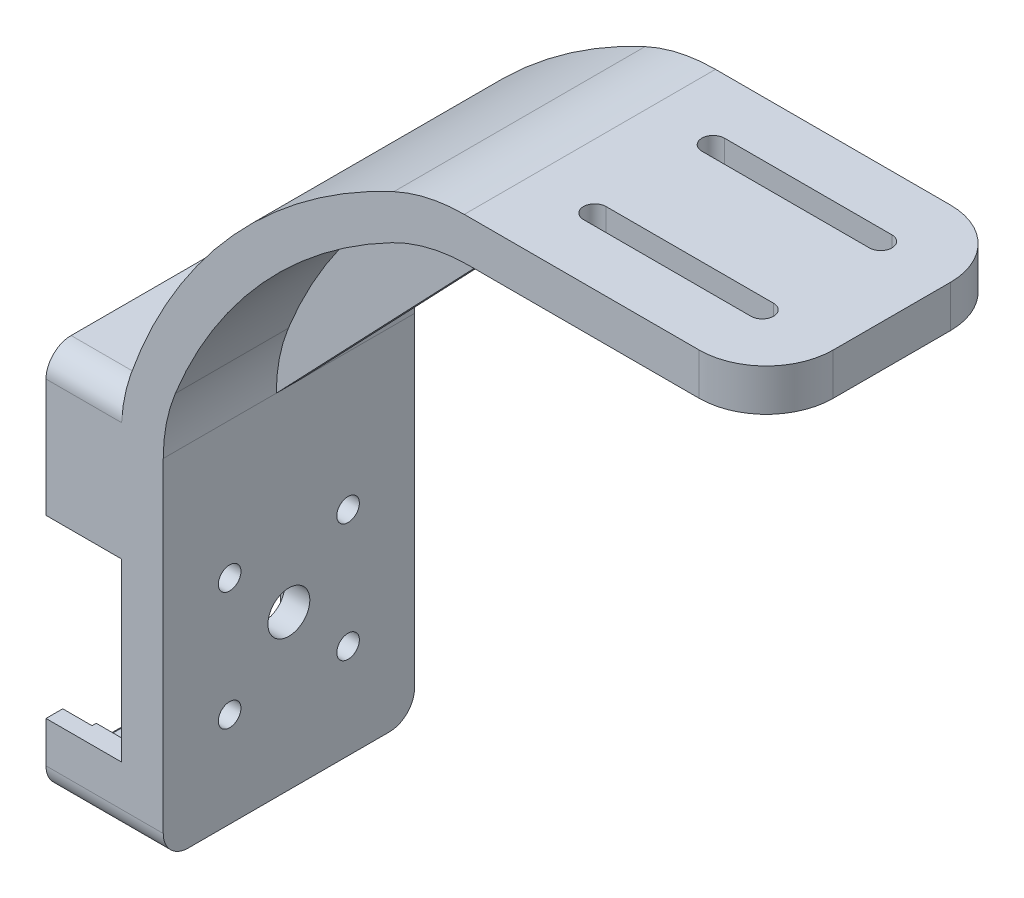
SolidWorks part; units mm, degrees
material "ABS"
ref_plane "Alzado" through (0, 0, 0) normal (0, 0, 1) x (1, 0, 0)
ref_plane "Planta" through (0, 0, 0) normal (0, 1, 0) x (1, 0, 0)
ref_plane "Vista lateral" through (0, 0, 0) normal (1, 0, 0) x (0, 0, -1)
sketch "Croquis1" plane through (0, 0, 0) normal (0, 0, 1) x (1, 0, 0)
  line L0 (7, 0) -> (7, 5)
  line L1 (7, 5) -> (-33, 5)
  line L2 (-33, 5) -> (-70, -35) construction
  line L3 (-70, -35) -> (-70, -80)
  line L4 (-70, -80) -> (-65, -80)
  line L5 (-65, -80) -> (-65, -34.8052)
  line L6 (-65, -34.8052) -> (-32.8052, 0) construction
  line L7 (-32.8052, 0) -> (7, 0)
  line L8 (-48.9026, -17.4026) -> (-12.1976, -51.3547) construction
  arc A0 (-33, 5) -> (-70, -35) centre (-12.1976, -51.3547) ccw
  arc A2 (-32.8052, 0) -> (-65, -34.8052) centre (-12.1976, -51.3547) ccw
  dimension "D1" = 5
  dimension "D2" = 37
  dimension "D4" = 5
  dimension "D5" = 40
  dimension "D6" = 45
  dimension "D7" = 40
  dimension "D8" = 50
extrude "Saliente-Extruir1" add sketch "Croquis1" along normal blind 30
sketch "Croquis2" plane through (0, 5, 0) normal (0, 1, 0) x (1, 0, 0)
  line L0 (7, -30) -> (7, 0) construction
  line L1 (-11.4, -15) -> (-11.4, -12) construction
  line L2 (-11.4, -12) -> (-4.4, -12) construction
  line L4 (-4.4, -18) -> (-18.4, -18) construction
  line L6 (-18.4, -12) -> (-11.4, -12) construction
  line L7 (-11.4, -15) -> (-11.4, -7.93) construction
  line L8 (-11.4, -7.93) -> (-11.4, -6.58) construction
  line L9 (-11.4, -6.58) -> (-1.4, -6.58)
  line L11 (-1.4, -9.28) -> (-21.4, -9.28)
  line L13 (-21.4, -6.58) -> (-11.4, -6.58)
  line L14 (-11.4, -15) -> (-21.0577, -15) construction
  line L15 (-1.4, -20.72) -> (-21.4, -20.72)
  line L16 (-11.4, -23.42) -> (-1.4, -23.42)
  line L17 (-21.4, -23.42) -> (-11.4, -23.42)
  line L18 (-11.4, -15) -> (7, -15) construction
  circle A0 centre (-11.4, -15) radius 18.4 construction
  arc A1 (-18.4, -18) -> (-18.4, -12) centre (-18.4, -15) cw construction
  arc A2 (-4.4, -18) -> (-4.4, -12) centre (-4.4, -15) ccw construction
  arc A3 (-1.4, -9.28) -> (-1.4, -6.58) centre (-1.4, -7.93) ccw
  arc A4 (-21.4, -9.28) -> (-21.4, -6.58) centre (-21.4, -7.93) cw
  arc A5 (-1.4, -20.72) -> (-1.4, -23.42) centre (-1.4, -22.07) cw
  arc A6 (-21.4, -20.72) -> (-21.4, -23.42) centre (-21.4, -22.07) ccw
  dimension "D1" = 36.8
  dimension "D5" = 3
  dimension "D6" = 3
  dimension "D11" = 1.35
  dimension "D12" = 1.35
  dimension "D2" = 18.4
  dimension "D3" = 3
  dimension "D4" = 6
  dimension "D7" = 7
  dimension "D8" = 7
  dimension "D9" = 7.07
  dimension "D10" = 2.7
  dimension "D13" = 10
  dimension "D14" = 10
extrude "Cortar-Extruir1" cut sketch "Croquis2" against normal up to vertex (5 mm away) up to point (7, 0, 30)
sketch "Croquis3" plane through (0, 0, 0) normal (0, -1, 0) x (1, 0, 0)
  line L0 (7, 30) -> (7, 0) construction
  line L5 (-21.4, 9.28) -> (-1.4, 9.28) construction
  line L6 (-26.4, 27.5) -> (3.6, 27.5)
  line L7 (-26.4, 27.5) -> (-26.4, 2.5)
  line L8 (-26.4, 2.5) -> (3.6, 2.5)
  line L9 (3.6, 27.5) -> (3.6, 2.5)
  line L10 (-26.4, 27.5) -> (3.6, 2.5) construction
  line L11 (-26.4, 2.5) -> (3.6, 27.5) construction
  line L12 (7, 15) -> (-11.4, 15) construction
  line L13 (-11.4, 15) -> (-11.4, 9.28) construction
  point P0 (-11.4, 15)
  dimension "D1" = 25
  dimension "D2" = 30
extrude "Cortar-Extruir2" cut sketch "Croquis3" against normal blind 2
sketch "Croquis4" plane through (-70, 0, 0) normal (-1, 0, 0) x (0, 0, 1)
  line L0 (30, -80) -> (0, -80) construction
  line L1 (15, -61.6) -> (21.5109, -61.6) construction
  line L3 (22.0711, -54.5289) -> (15, -61.6) construction
  circle A0 centre (15, -61.6) radius 18.4 construction
  circle A1 centre (22.0711, -54.5289) radius 1.35
  circle A2 centre (22.0711, -68.6711) radius 1.35
  circle A3 centre (7.9289, -68.6711) radius 1.35
  circle A4 centre (7.9289, -54.5289) radius 1.35
  circle A5 centre (15, -61.6) radius 2.5
  point P15 (15, -61.6)
  dimension "D1" = 36.8
  dimension "D5" = 2.7
  dimension "D7" = 5
  dimension "D2" = 18.4
  dimension "D3" = 45
  dimension "D4" = 10
  dimension "D6" = 4
extrude "Cortar-Extruir3" cut sketch "Croquis4" against normal up to vertex (5 mm away) up to point (-65, -80, 30)
sketch "Croquis5" plane through (-70, 0, 0) normal (-1, 0, 0) x (0, 0, 1)
  line L0 (15, -61.6) -> (15, -59.1) construction
  line L1 (2.5, -74.1) -> (27.5, -74.1)
  line L2 (2.5, -74.1) -> (2.5, -49.1)
  line L3 (2.5, -49.1) -> (27.5, -49.1)
  line L4 (27.5, -74.1) -> (27.5, -49.1)
  line L5 (2.5, -74.1) -> (27.5, -49.1) construction
  line L6 (2.5, -49.1) -> (27.5, -74.1) construction
  line L8 (17.5, -61.6) -> (15, -61.6) construction
  circle A0 centre (15, -61.6) radius 2.5 construction
  point P0 (15, -61.6)
  dimension "D1" = 25
  dimension "D2" = 25
extrude "Cortar-Extruir4" cut sketch "Croquis5" against normal blind 2
fillet "Redondeo2" radius 20 4 edges at (-70, -35, 15) (-33, 5, 15) (-32.8052, 0, 15) (-65, -34.8052, 15)
fillet "Redondeo3" radius 8 2 edges at (7, 2.5, 0) (7, 2.5, 30)
fillet "Redondeo4" radius 2 8 edges at (-26.4, 1, 2.5) (3.6, 1, 2.5) (3.6, 1, 27.5) (-26.4, 1, 27.5) (-69, -74.1, 2.5) (-69, -49.1, 2.5) (-69, -49.1, 27.5) (-69, -74.1, 27.5)
sketch "Croquis6" plane through (-68, 0, 0) normal (-1, 0, 0) x (0, 0, 1)
  line L26 (4.5, -74.1) -> (25.5, -74.1)
  line L27 (2.5, -51.1) -> (2.5, -72.1)
  line L28 (27.5, -72.1) -> (27.5, -51.1)
  line L29 (25.5, -49.1) -> (4.5, -49.1)
  line L30 (4.5, -74.1) -> (25.5, -74.1)
  line L31 (2.5, -51.1) -> (2.5, -72.1)
  line L32 (27.5, -72.1) -> (27.5, -51.1)
  line L33 (25.5, -49.1) -> (4.5, -49.1)
  circle A0 centre (7.9289, -54.5289) radius 1.4425
  circle A1 centre (15, -61.6) radius 2.5
  circle A2 centre (22.0711, -54.5289) radius 1.35
  circle A3 centre (7.9289, -68.6711) radius 1.35
  circle A4 centre (22.0711, -68.6711) radius 1.35
  arc A29 (25.5, -74.1) -> (27.5, -72.1) centre (25.5, -72.1) ccw
  arc A30 (2.5, -72.1) -> (4.5, -74.1) centre (4.5, -72.1) ccw
  arc A31 (4.5, -49.1) -> (2.5, -51.1) centre (4.5, -51.1) ccw
  arc A32 (27.5, -51.1) -> (25.5, -49.1) centre (25.5, -51.1) ccw
  arc A33 (25.5, -74.1) -> (27.5, -72.1) centre (25.5, -72.1) ccw
  arc A34 (2.5, -72.1) -> (4.5, -74.1) centre (4.5, -72.1) ccw
  arc A35 (4.5, -49.1) -> (2.5, -51.1) centre (4.5, -51.1) ccw
  arc A36 (27.5, -51.1) -> (25.5, -49.1) centre (25.5, -51.1) ccw
  dimension "D1" = 0
sketch "Croquis8" plane through (-70, 0, 0) normal (-1, 0, 0) x (0, 0, 1)
  line L0 (15, -80) -> (15, -70.3427) construction
  line L1 (2.5, -37) -> (27.5, -37) construction
  line L2 (2.5, -37) -> (2.5, -77) construction
  line L3 (2.5, -77) -> (27.5, -77) construction
  line L4 (27.5, -37) -> (27.5, -77) construction
  line L5 (30, -80) -> (0, -80) construction
  line L6 (5.5, -40) -> (5.5, -74) construction
  line L7 (5.5, -74) -> (24.5, -74) construction
  line L8 (24.5, -40) -> (24.5, -74) construction
  line L9 (5.5, -40) -> (24.5, -40) construction
  line L10 (2.5, -72.1) -> (0, -72.1)
  line L11 (0, -38.0615) -> (0, -80) construction
  line L12 (0, -72.1) -> (0, -80)
  line L13 (0, -80) -> (30, -80)
  line L14 (30, -80) -> (30, -72.1)
  line L15 (30, -38.0615) -> (30, -80) construction
  line L16 (30, -72.1) -> (27.5, -72.1)
  line L17 (2.5, -51.1) -> (0, -51.1)
  line L18 (0, -51.1) -> (0, -34)
  line L19 (0, -34) -> (30, -34)
  line L20 (30, -34) -> (30, -51.1)
  line L21 (30, -51.1) -> (27.5, -51.1)
  line L25 (25.5, -49.1) -> (4.5, -49.1)
  line L26 (25.5, -49.1) -> (4.5, -49.1)
  line L29 (4.5, -74.1) -> (25.5, -74.1)
  line L30 (4.5, -74.1) -> (25.5, -74.1)
  circle A0 centre (24.5, -68.5) radius 1.5 construction
  circle A1 centre (5.5, -45.5) radius 1.5 construction
  arc A8 (27.5, -51.1) -> (25.5, -49.1) centre (25.5, -51.1) ccw
  arc A9 (4.5, -49.1) -> (2.5, -51.1) centre (4.5, -51.1) ccw
  arc A10 (27.5, -51.1) -> (25.5, -49.1) centre (25.5, -51.1) ccw
  arc A11 (4.5, -49.1) -> (2.5, -51.1) centre (4.5, -51.1) ccw
  arc A16 (25.5, -74.1) -> (27.5, -72.1) centre (25.5, -72.1) ccw
  arc A17 (2.5, -72.1) -> (4.5, -74.1) centre (4.5, -72.1) ccw
  arc A18 (25.5, -74.1) -> (27.5, -72.1) centre (25.5, -72.1) ccw
  arc A19 (2.5, -72.1) -> (4.5, -74.1) centre (4.5, -72.1) ccw
  point P12 (15, -77)
  dimension "D3" = 3
  dimension "D5" = 3
  dimension "D8" = 3
  dimension "D1" = 25
  dimension "D2" = 40
  dimension "D4" = 8.5
  dimension "D6" = 19
  dimension "D7" = 23
  dimension "D10" = 3
  dimension "D11" = 3
  dimension "D9" = 3
  dimension "D12" = 0
  dimension "D13" = 0
extrude "Saliente-Extruir2" add sketch "Croquis8" along normal blind 9 and the other way blind 1
sketch "Croquis10" plane through (-70, 0, 0) normal (-1, 0, 0) x (0, 0, 1)
  line L0 (2, -36.5) -> (2, -51.1)
  line L5 (2.5, -37) -> (27.5, -37) construction
  line L6 (2.5, -37) -> (2.5, -51.1) construction
  line L7 (2.5, -51.1) -> (27.5, -51.1) construction
  line L8 (27.5, -37) -> (27.5, -51.1) construction
  line L9 (2, -36.5) -> (28, -36.5)
  line L10 (28, -36.5) -> (28, -51.1)
  line L11 (2, -51.1) -> (28, -51.1)
  dimension "D1" = 0.5
extrude "Cortar-Extruir5" cut sketch "Croquis10" against normal blind 5 from surface at 9 starting at face at (-79, -46.2214, 15)
sketch "Croquis12" plane through (-70, 0, 0) normal (-1, 0, 0) x (0, 0, 1)
  line L0 (2.5, -51.1) -> (2.5, -41.3418) construction
  circle A0 centre (5.5, -45.5) radius 2.1
  circle A1 centre (5.5, -45.5) radius 3.6
  dimension "D1" = 4.2
  dimension "D2" = 7.2
extrude "Saliente-Extruir3" add sketch "Croquis12" along normal blind 3 from surface at 4 starting at face at (-74, -46.8464, 15)
sketch "Croquis13" plane through (-74, 0, 0) normal (-1, 0, 0) x (0, 0, 1)
  circle A0 centre (5.5, -45.5) radius 2.1
extrude "Cortar-Extruir7" cut sketch "Croquis13" against normal blind 5 from surface at 3 starting at face at (-77, -45.5, 5.55)
sketch "Croquis14" plane through (-70, 0, 0) normal (-1, 0, 0) x (0, 0, 1)
  line L0 (2, -72.1) -> (2, -77.5)
  line L1 (2.5, -72.1) -> (27.5, -72.1) construction
  line L2 (2.5, -72.1) -> (2.5, -77) construction
  line L3 (2.5, -77) -> (27.5, -77) construction
  line L4 (27.5, -72.1) -> (27.5, -77) construction
  line L5 (2, -77.5) -> (28, -77.5)
  line L6 (28, -72.1) -> (28, -77.5)
  line L7 (2, -72.1) -> (28, -72.1)
  dimension "D1" = 0.5
extrude "Cortar-Extruir8" cut sketch "Croquis14" against normal blind 3.5 from surface at 9 starting at face at (-79, -74.6786, 15)
fillet "Redondeo5" radius 3 4 edges at (-72, -80, 30) (-72, -80, 0) (-74.2916, -34, 0) (-74.2916, -34, 30)
sketch "Croquis15" plane through (0, 0, 30) normal (0, 0, 1) x (1, 0, 0)
  line L0 (-65, -38.2179) -> (-28.4904, 0)
  arc A9 (-28.4904, 0) -> (-37.7123, -2.253) centre (-28.4904, -20) ccw
  arc A10 (-37.7123, -2.253) -> (-63.5664, -30.7823) centre (-12.1976, -51.3547) ccw
  arc A11 (-63.5664, -30.7823) -> (-65, -38.2179) centre (-45, -38.2179) ccw
  arc A12 (-28.4904, 0) -> (-37.7123, -2.253) centre (-28.4904, -20) ccw
  arc A13 (-37.7123, -2.253) -> (-63.5664, -30.7823) centre (-12.1976, -51.3547) ccw
  arc A14 (-63.5664, -30.7823) -> (-65, -38.2179) centre (-45, -38.2179) ccw
  dimension "D1" = 0
extrude "Saliente-Extruir4" add sketch "Croquis15" against normal blind 1.5 and the other way blind 1.5 from offset 15
